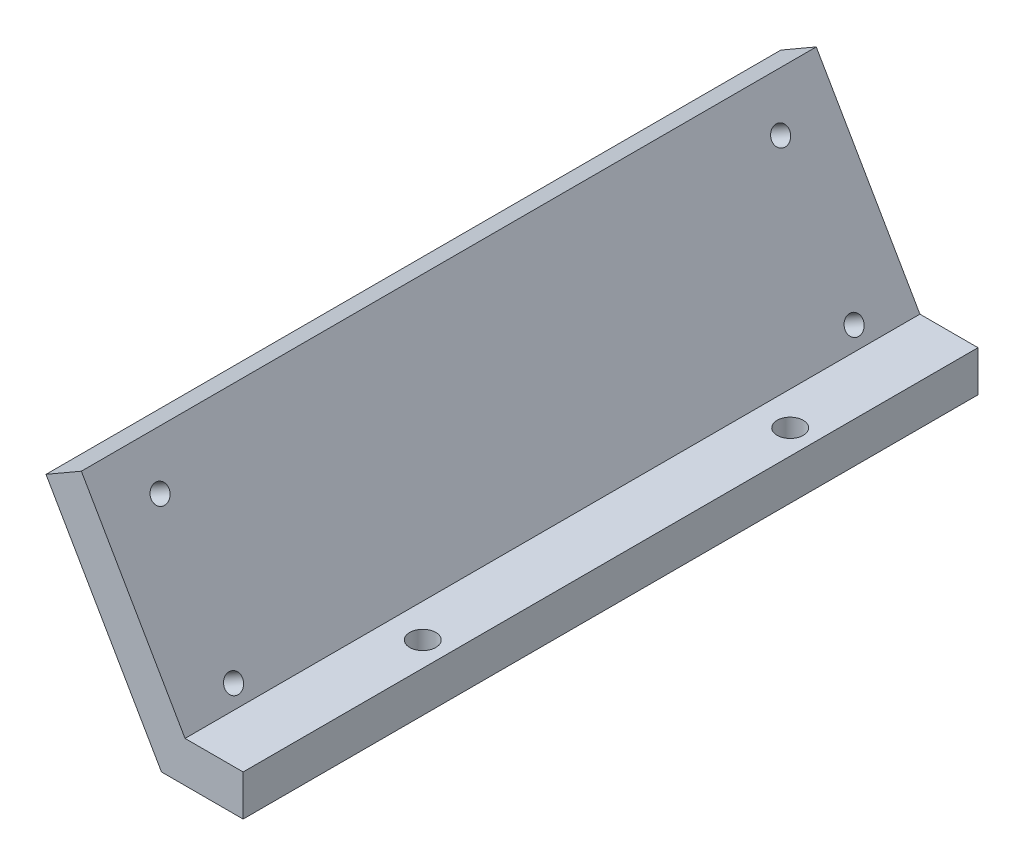
SolidWorks part; units mm, degrees
ref_plane "前视基准面" through (0, 0, 0) normal (0, 0, 1) x (1, 0, 0)
ref_plane "上视基准面" through (0, 0, 0) normal (0, 1, 0) x (1, 0, 0)
ref_plane "右视基准面" through (0, 0, 0) normal (1, 0, 0) x (0, 0, -1)
sketch "草图1" plane through (0, 0, 0) normal (0, 0, 1) x (1, 0, 0)
  line L0 (0, 0) -> (-14.1421, 24.4949)
  line L1 (0, 0) -> (10, 0)
  line L2 (2.8868, 5) -> (-9.812, 26.9949)
  line L3 (2.8868, 5) -> (10, 5)
  line L4 (10, 5) -> (10, 0)
  line L5 (-9.812, 26.9949) -> (-14.1421, 24.4949)
  dimension "D1" = 5
extrude "凸台-拉伸1" add sketch "草图1" along normal blind 90
sketch "草图2" plane through (0, 5, 0) normal (0, 1, 0) x (1, 0, 0)
  circle A3 centre (7, -20) radius 1.6
  circle A4 centre (7, -65) radius 1.6
extrude "切除-拉伸1" cut sketch "草图2" against normal blind 10
sketch "草图3" plane through (0, 0, 0) normal (-0.866, -0.5, 0) x (0, 0, 1)
  circle A0 centre (7, 23) radius 1.1
  circle A1 centre (83, 23) radius 1.1
  circle A2 centre (83, 5) radius 1.1
  circle A3 centre (7, 5) radius 1.1
  dimension "D1" = 2
  dimension "D2" = 2
extrude "切除-拉伸2" cut sketch "草图3" against normal blind 10
